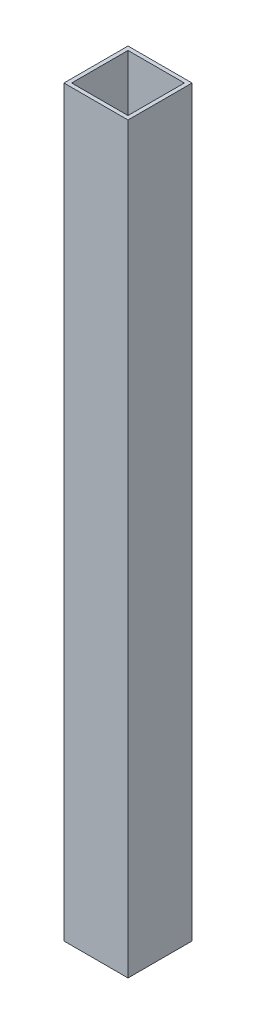
SolidWorks part; units mm, degrees
ref_plane "Front Plane" through (0, 0, 0) normal (0, 0, 1) x (1, 0, 0)
ref_plane "Top Plane" through (0, 0, 0) normal (0, 1, 0) x (1, 0, 0)
ref_plane "Right Plane" through (0, 0, 0) normal (1, 0, 0) x (0, 0, -1)
sketch "Sketch1" plane through (0, 0, 0) normal (0, 1, 0) x (1, 0, 0)
  line L0 (-26.6278, 1.8372) -> (-14.1278, -10.6628) construction
  line L1 (-26.6278, 1.8372) -> (-14.1278, 1.8372)
  line L2 (-26.6278, 1.8372) -> (-26.6278, -10.6628)
  line L3 (-26.6278, -10.6628) -> (-14.1278, -10.6628)
  line L4 (-14.1278, 1.8372) -> (-14.1278, -10.6628)
  line L5 (-26.6278, -10.6628) -> (-14.1278, 1.8372) construction
  line L7 (-25.8778, 1.0872) -> (-14.8778, 1.0872)
  line L8 (-25.8778, 1.0872) -> (-25.8778, -9.9128)
  line L9 (-25.8778, -9.9128) -> (-14.8778, -9.9128)
  line L10 (-14.8778, 1.0872) -> (-14.8778, -9.9128)
  line L11 (-25.8778, 1.0872) -> (-14.8778, -9.9128) construction
  line L12 (-25.8778, -9.9128) -> (-14.8778, 1.0872) construction
  point P4 (-20.3778, -4.4128)
extrude "Boss-Extrude3" add sketch "Sketch1" along normal blind 145
